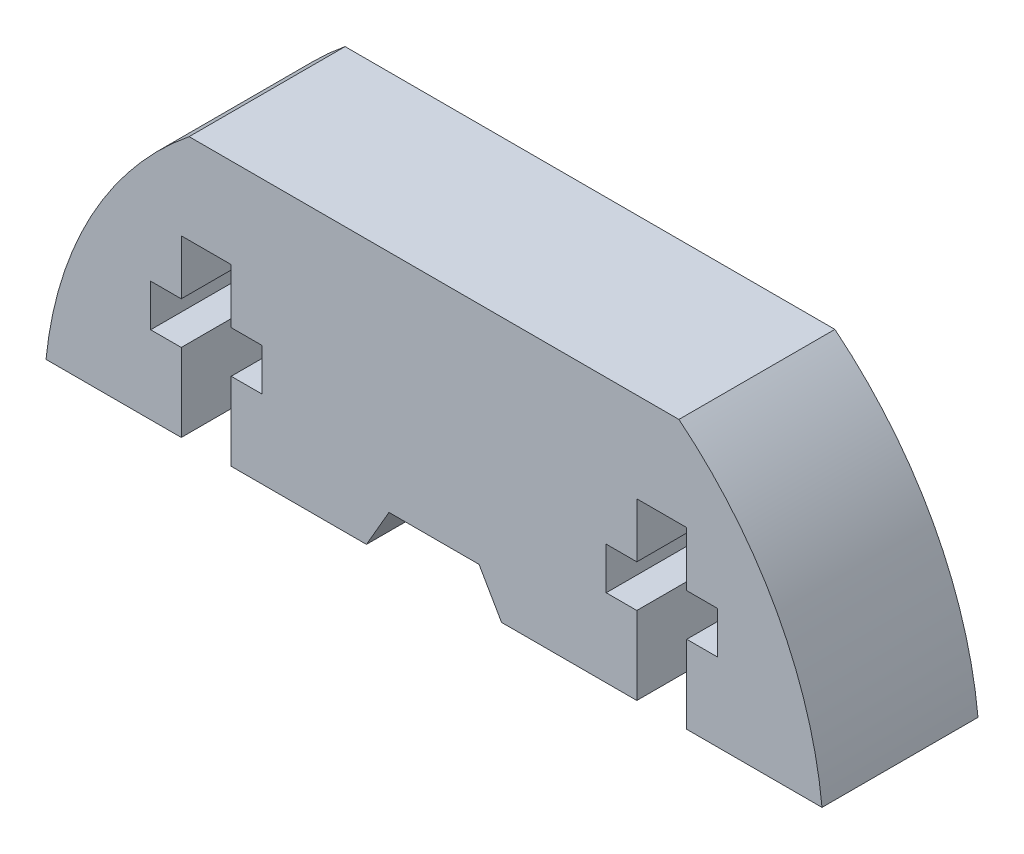
SolidWorks part; units mm, degrees
ref_plane "Front Plane" through (0, 0, 0) normal (0, 0, 1) x (1, 0, 0)
ref_plane "Top Plane" through (0, 0, 0) normal (0, 1, 0) x (1, 0, 0)
ref_plane "Right Plane" through (0, 0, 0) normal (1, 0, 0) x (0, 0, -1)
sketch "Sketch2" plane through (0, 0, 0) normal (0, 0, 1) x (1, 0, 0)
  line L0 (-4.3301, 2.5) -> (-24.8747, 2.5)
  line L1 (5.7735, 0) -> (2.8868, 5)
  line L2 (2.8868, 5) -> (-2.8868, 5)
  line L3 (-2.8868, 5) -> (-5.7735, 0)
  line L4 (-5.7735, 0) -> (-2.8868, -5)
  line L5 (-2.8868, -5) -> (2.8868, -5)
  line L6 (2.8868, -5) -> (5.7735, 0)
  line L7 (4.3301, 2.5) -> (24.8747, 2.5)
  line L8 (-15.7007, 19.4548) -> (15.7007, 19.4548)
  line L9 (0, 0) -> (0, 25)
  line L10 (16.2024, -8.7) -> (13.0024, -8.7)
  line L11 (16.2024, -8.7) -> (16.2024, 13.7)
  line L12 (16.2024, 13.7) -> (13.0024, 13.7)
  line L13 (13.0024, -8.7) -> (13.0024, 13.7)
  line L14 (16.2024, -8.7) -> (13.0024, 13.7) construction
  line L15 (16.2024, 13.7) -> (13.0024, -8.7) construction
  line L16 (11.0396, 7.5) -> (18.1652, 7.5)
  line L17 (11.0396, 7.5) -> (11.0396, 10.2)
  line L18 (11.0396, 10.2) -> (18.1652, 10.2)
  line L19 (18.1652, 7.5) -> (18.1652, 10.2)
  line L20 (11.0396, 7.5) -> (18.1652, 10.2) construction
  line L21 (11.0396, 10.2) -> (18.1652, 7.5) construction
  line L22 (-18.1652, 7.5) -> (-18.1652, 10.2)
  line L23 (-16.2024, -8.7) -> (-13.0024, -8.7)
  line L24 (-16.2024, -8.7) -> (-16.2024, 13.7)
  line L25 (-11.0396, 7.5) -> (-18.1652, 10.2) construction
  line L26 (-11.0396, 10.2) -> (-18.1652, 7.5) construction
  line L27 (-16.2024, 13.7) -> (-13.0024, -8.7) construction
  line L28 (-16.2024, -8.7) -> (-13.0024, 13.7) construction
  line L29 (-11.0396, 7.5) -> (-18.1652, 7.5)
  line L30 (-11.0396, 7.5) -> (-11.0396, 10.2)
  line L31 (-11.0396, 10.2) -> (-18.1652, 10.2)
  line L32 (-13.0024, -8.7) -> (-13.0024, 13.7)
  line L33 (-16.2024, 13.7) -> (-13.0024, 13.7)
  circle A0 centre (0, 0) radius 5 construction
  circle A1 centre (0, 0) radius 25
  point P16 (14.6024, 2.5)
  point P21 (14.6024, 8.85)
  point P29 (-14.6024, 2.5)
  point P35 (-14.6024, 8.85)
  dimension "D2" = 5
  dimension "D1" = 10
  dimension "D3" = 2.7
  dimension "D4" = 3.5
extrude "Boss-Extrude2" add sketch "Sketch2" along normal blind 10 contours L7 A1 L8 L9 L2 L1 L13 L16 L17 L18 L12 L11 L19 | L8 A1 L0 L24 L29 L22 L31 L33 L32 L30 L3 L2 L9
